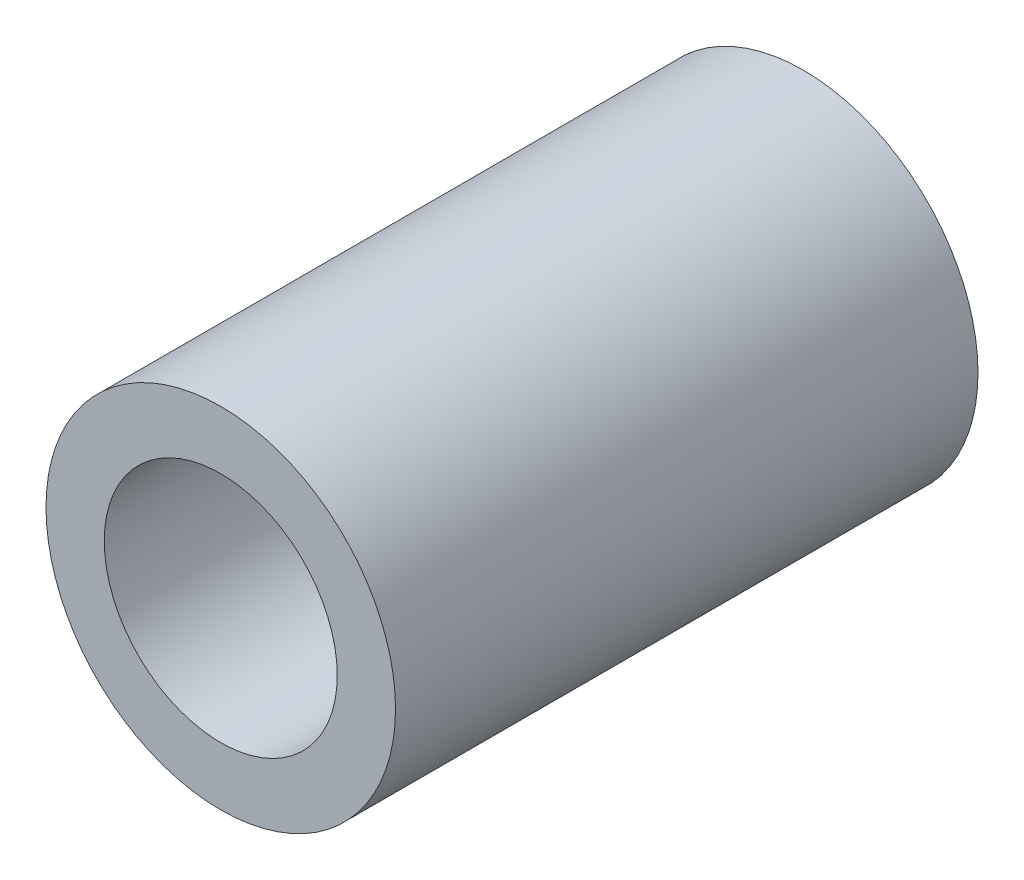
SolidWorks part; units mm, degrees
ref_plane "前视基准面" through (0, 0, 0) normal (0, 0, 1) x (1, 0, 0)
ref_plane "上视基准面" through (0, 0, 0) normal (0, 1, 0) x (1, 0, 0)
ref_plane "右视基准面" through (0, 0, 0) normal (1, 0, 0) x (0, 0, -1)
sketch "草图1" plane through (0, 0, 0) normal (0, 0, 1) x (1, 0, 0)
  circle A0 centre (0, 0) radius 3
  circle A1 centre (0, 0) radius 2
  dimension "D1" = 4
  dimension "D2" = 6
extrude "凸台-拉伸1" add sketch "草图1" along normal mid plane 10
